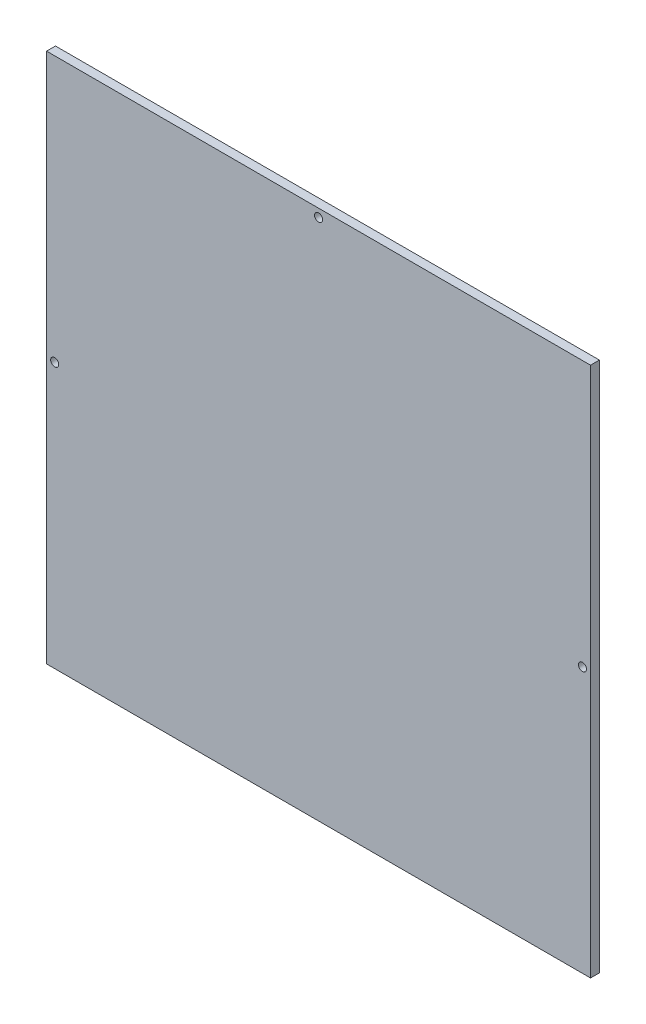
SolidWorks part; units mm, degrees
ref_plane "Front" through (0, 0, 0) normal (0, 0, 1) x (1, 0, 0)
ref_plane "Top" through (0, 0, 0) normal (0, 1, 0) x (1, 0, 0)
ref_plane "Right" through (0, 0, 0) normal (1, 0, 0) x (0, 0, -1)
sketch "Sketch1" plane through (0, 0, 0) normal (0, 0, 1) x (1, 0, 0)
  line L0 (0, -55) -> (0, 55) construction
  line L1 (-101.1, 98.64) -> (101.1, 98.64)
  line L2 (-101.1, 98.64) -> (-101.1, -98.64)
  line L3 (-101.1, -98.64) -> (101.1, -98.64)
  line L4 (101.1, 98.64) -> (101.1, -98.64)
  line L5 (-101.1, 98.64) -> (101.1, -98.64) construction
  line L6 (-101.1, -98.64) -> (101.1, 98.64) construction
  line L7 (55, 0) -> (-55, 0) construction
  circle A0 centre (0, 95.64) radius 1.5
  circle A1 centre (-98.1, 0) radius 1.5
  circle A2 centre (98.1, 0) radius 1.5
  point P0 (0, 0)
  point P14 (0, 0)
  dimension "D1" = 3
  dimension "D2" = 95.64
  dimension "D4" = 3
  dimension "D5" = 98.1
  dimension "D3" = 3
extrude "Boss-Extrude1" add sketch "Sketch1" along normal blind 3.3
